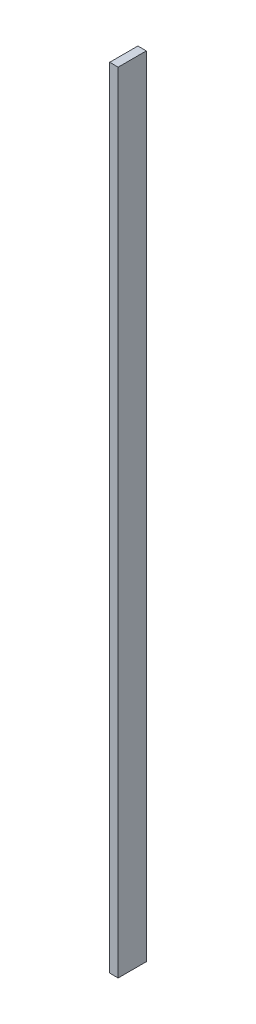
SolidWorks part; units mm, degrees
ref_plane "前视基准面" through (0, 0, 0) normal (0, 0, 1) x (1, 0, 0)
ref_plane "上视基准面" through (0, 0, 0) normal (0, 1, 0) x (1, 0, 0)
ref_plane "右视基准面" through (0, 0, 0) normal (1, 0, 0) x (0, 0, -1)
other "Configuration Table"
sketch "草图1" plane through (0, 0, 0) normal (1, 0, 0) x (0, 0, -1)
  line L1 (-18.076, 60.9866) -> (-8.076, 60.9866)
  line L2 (-18.076, 60.9866) -> (-18.076, -219.0134)
  line L3 (-18.076, -219.0134) -> (-8.076, -219.0134)
  line L4 (-8.076, 60.9866) -> (-8.076, -219.0134)
  dimension "D1" = 280
  dimension "D2" = 10
extrude "凸台-拉伸1" add sketch "草图1" along normal blind 3
